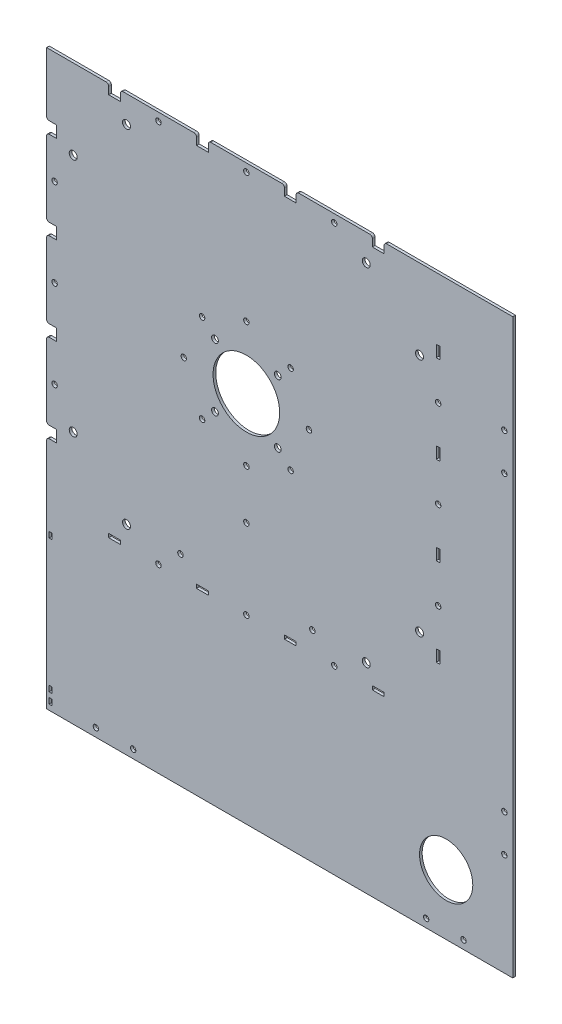
SolidWorks part; units mm, degrees
ref_plane "前视基准面" through (0, 0, 0) normal (0, 0, 1) x (1, 0, 0)
ref_plane "上视基准面" through (0, 0, 0) normal (0, 1, 0) x (1, 0, 0)
ref_plane "右视基准面" through (0, 0, 0) normal (1, 0, 0) x (0, 0, -1)
sketch "草图1" plane through (0, 0, 0) normal (0, 0, 1) x (1, 0, 0)
  line L0 (1.4571, -21.1871) -> (1.4571, -41.1871) construction
  line L2 (1.4571, -21.1871) -> (1.4571, 44.8129) construction
  line L4 (151.4571, -41.1871) -> (151.4571, 108.8129)
  line L5 (151.4571, 108.8129) -> (-148.5429, 108.8129)
  line L6 (-148.5429, 108.8129) -> (-148.5429, -191.1871)
  line L7 (-148.5429, -191.1871) -> (151.4571, -191.1871)
  line L8 (151.4571, -191.1871) -> (151.4571, -41.1871)
  line L9 (-148.5429, -41.1871) -> (-161.9412, -41.1871) construction
  line L10 (1.4571, -191.1871) -> (1.4571, -181.0361) construction
  circle A6 centre (1.4571, -21.1871) radius 241.4173 construction
  circle A9 centre (1.4571, -41.1871) radius 25
  circle A10 centre (25.0271, -17.6171) radius 2.55
  circle A11 centre (25.0271, -64.7571) radius 2.55
  circle A12 centre (-22.1129, -64.7571) radius 2.55
  circle A13 centre (-22.1129, -17.6171) radius 2.55
  circle A14 centre (115.1844, -53.0393) radius 12.2821 construction
  dimension "D1" = 50
  dimension "D4" = 5.1
  dimension "D2" = 300
  dimension "D3" = 300
  dimension "D5" = 23.57
  dimension "D6" = 23.57
  dimension "D7" = 4
extrude "凸台-拉伸1" add sketch "草图1" along normal blind 2
sketch "草图3" plane through (0, 0, 2) normal (0, 0, 1) x (1, 0, 0)
  line L1 (96.0571, -183.7871) -> (104.8571, -183.7871)
  line L13 (1.4571, -191.1871) -> (1.4571, -185.1871) construction
  line L14 (-148.5429, -191.1871) -> (151.4571, -191.1871) construction
  line L15 (1.4571, -185.1871) -> (34.4571, -185.1871) construction
  line L16 (34.4571, -185.1871) -> (67.4571, -185.1871) construction
  line L17 (30.0571, -183.7871) -> (38.8571, -183.7871)
  line L18 (30.0571, -183.7871) -> (30.0571, -186.5871)
  line L19 (30.0571, -186.5871) -> (38.8571, -186.5871)
  line L20 (38.8571, -183.7871) -> (38.8571, -186.5871)
  line L21 (30.0571, -183.7871) -> (38.8571, -186.5871) construction
  line L22 (30.0571, -186.5871) -> (38.8571, -183.7871) construction
  line L23 (67.4571, -185.1871) -> (100.4571, -185.1871) construction
  line L24 (96.0571, -183.7871) -> (96.0571, -186.5871)
  line L25 (96.0571, -186.5871) -> (104.8571, -186.5871)
  line L26 (96.0571, -186.5871) -> (104.8571, -183.7871) construction
  line L27 (104.8571, -186.5871) -> (104.8571, -183.7871)
  line L28 (-35.9429, -183.7871) -> (-35.9429, -186.5871)
  line L29 (-27.1429, -183.7871) -> (-35.9429, -183.7871)
  line L30 (-27.1429, -183.7871) -> (-27.1429, -186.5871)
  line L31 (-27.1429, -186.5871) -> (-35.9429, -186.5871)
  line L32 (-93.1429, -183.7871) -> (-93.1429, -186.5871)
  line L33 (-101.9429, -186.5871) -> (-101.9429, -183.7871)
  line L34 (-93.1429, -183.7871) -> (-101.9429, -183.7871)
  line L35 (-93.1429, -186.5871) -> (-101.9429, -186.5871)
  line L36 (-141.1429, 53.4129) -> (-141.1429, 62.2129)
  line L37 (-143.9429, 53.4129) -> (-143.9429, 62.2129)
  line L38 (-143.9429, 62.2129) -> (-141.1429, 62.2129)
  line L39 (-141.1429, 53.4129) -> (-143.9429, 53.4129)
  line L40 (-141.1429, -12.5871) -> (-141.1429, -3.7871)
  line L41 (-141.1429, -3.7871) -> (-143.9429, -3.7871)
  line L42 (-143.9429, -12.5871) -> (-143.9429, -3.7871)
  line L43 (-141.1429, -12.5871) -> (-143.9429, -12.5871)
  line L44 (-141.1429, -69.7871) -> (-143.9429, -69.7871)
  line L45 (-141.1429, -69.7871) -> (-141.1429, -78.5871)
  line L46 (-143.9429, -69.7871) -> (-143.9429, -78.5871)
  line L47 (-141.1429, -78.5871) -> (-143.9429, -78.5871)
  line L48 (-141.1429, -135.7871) -> (-141.1429, -144.5871)
  line L49 (-143.9429, -135.7871) -> (-143.9429, -144.5871)
  line L50 (-141.1429, -135.7871) -> (-143.9429, -135.7871)
  line L51 (-143.9429, -144.5871) -> (-141.1429, -144.5871)
  line L52 (96.0571, 101.4129) -> (104.8571, 101.4129)
  line L53 (96.0571, 104.2129) -> (104.8571, 104.2129)
  line L54 (104.8571, 104.2129) -> (104.8571, 101.4129)
  line L55 (96.0571, 101.4129) -> (96.0571, 104.2129)
  line L56 (30.0571, 101.4129) -> (38.8571, 101.4129)
  line L57 (38.8571, 101.4129) -> (38.8571, 104.2129)
  line L58 (30.0571, 104.2129) -> (38.8571, 104.2129)
  line L59 (30.0571, 101.4129) -> (30.0571, 104.2129)
  line L60 (-27.1429, 101.4129) -> (-27.1429, 104.2129)
  line L61 (-27.1429, 101.4129) -> (-35.9429, 101.4129)
  line L62 (-27.1429, 104.2129) -> (-35.9429, 104.2129)
  line L63 (-35.9429, 101.4129) -> (-35.9429, 104.2129)
  line L64 (-93.1429, 101.4129) -> (-101.9429, 101.4129)
  line L65 (-93.1429, 104.2129) -> (-101.9429, 104.2129)
  line L66 (-93.1429, 101.4129) -> (-93.1429, 104.2129)
  line L67 (-101.9429, 104.2129) -> (-101.9429, 101.4129)
  line L68 (144.0571, -135.7871) -> (144.0571, -144.5871)
  line L69 (146.8571, -135.7871) -> (146.8571, -144.5871)
  line L70 (146.8571, -144.5871) -> (144.0571, -144.5871)
  line L71 (144.0571, -135.7871) -> (146.8571, -135.7871)
  line L72 (144.0571, -69.7871) -> (144.0571, -78.5871)
  line L73 (144.0571, -78.5871) -> (146.8571, -78.5871)
  line L74 (146.8571, -69.7871) -> (146.8571, -78.5871)
  line L75 (144.0571, -69.7871) -> (146.8571, -69.7871)
  line L76 (144.0571, -12.5871) -> (146.8571, -12.5871)
  line L77 (144.0571, -12.5871) -> (144.0571, -3.7871)
  line L78 (146.8571, -12.5871) -> (146.8571, -3.7871)
  line L79 (144.0571, -3.7871) -> (146.8571, -3.7871)
  line L80 (144.0571, 53.4129) -> (144.0571, 62.2129)
  line L81 (146.8571, 53.4129) -> (146.8571, 62.2129)
  line L82 (144.0571, 53.4129) -> (146.8571, 53.4129)
  line L83 (146.8571, 62.2129) -> (144.0571, 62.2129)
  line L84 (50.9571, -185.1871) -> (50.9571, -170.1871) construction
  line L85 (17.9571, -185.1871) -> (17.9571, -170.1871) construction
  line L86 (-48.0429, -170.1871) -> (-15.0429, -170.1871) construction
  line L91 (-31.5429, -170.1871) -> (-31.5429, -155.1871) construction
  line L92 (100.4571, -185.1871) -> (104.8571, -186.5871) construction
  line L93 (-31.5429, -155.1871) -> (1.4571, -155.1871) construction
  line L95 (1.4571, -155.1871) -> (34.4571, -155.1871) construction
  circle A0 centre (1.4571, -185.1871) radius 2.05
  circle A1 centre (67.4571, -185.1871) radius 2.05
  circle A2 centre (-64.5429, -185.1871) radius 2.05
  circle A3 centre (-142.5429, 24.8129) radius 2.05
  circle A4 centre (-142.5429, -41.1871) radius 2.05
  circle A5 centre (-142.5429, -107.1871) radius 2.05
  circle A6 centre (67.4571, 102.8129) radius 2.05
  circle A7 centre (1.4571, 102.8129) radius 2.05
  circle A8 centre (-64.5429, 102.8129) radius 2.05
  circle A9 centre (145.4571, -107.1871) radius 2.05
  circle A10 centre (145.4571, -41.1871) radius 2.05
  circle A11 centre (145.4571, 24.8129) radius 2.05
  circle A15 centre (17.9571, -170.1871) radius 2 construction
  circle A16 centre (-15.0429, -170.1871) radius 2 construction
  circle A17 centre (50.9571, -170.1871) radius 2.05
  circle A18 centre (-48.0429, -170.1871) radius 2.05
  circle A19 centre (-31.5429, -155.1871) radius 2.05 construction
  circle A20 centre (34.4571, -155.1871) radius 2.05 construction
  circle A22 centre (1.4571, -155.1871) radius 2 construction
  circle A23 centre (1.4571, -41.1871) radius 47 construction
  circle A24 centre (1.4571, -88.1871) radius 2.05
  circle A25 centre (-31.7769, -74.4212) radius 2.05
  circle A26 centre (-45.5429, -41.1871) radius 2.05
  circle A27 centre (-31.7769, -7.9531) radius 2.05
  circle A28 centre (1.4571, 5.8129) radius 2.05
  circle A29 centre (34.6912, -7.9531) radius 2.05
  circle A30 centre (48.4571, -41.1871) radius 2.05
  circle A31 centre (34.6912, -74.4212) radius 2.05
  circle A32 centre (1.4571, -125.1871) radius 2.05
  dimension "D1" = 8.8
  dimension "D3" = 4
  dimension "D4" = 8
  dimension "D5" = 30
  dimension "D6" = 4.1
  dimension "D7" = 94
  dimension "D8" = 4.1
  dimension "D9" = 8.8
  dimension "D2" = 2.8
  dimension "D10" = 2.8
extrude "切除-拉伸2" cut sketch "草图3" against normal blind 4
sketch "草图6" plane through (0, 0, 2) normal (0, 0, 1) x (1, 0, 0)
sketch "草图7" plane through (0, 0, 2) normal (0, 0, 1) x (1, 0, 0)
  line L5 (-148.5429, -171.1871) -> (151.4571, -171.1871) construction
  line L6 (-148.5429, 108.8129) -> (-148.5429, -191.1871) construction
  line L7 (151.4571, -191.1871) -> (151.4571, 108.8129) construction
  line L8 (-148.5429, -191.1871) -> (151.4571, -191.1871) construction
  circle A0 centre (-88.5429, -171.1871) radius 3
  circle A1 centre (91.4571, -171.1871) radius 3
  circle A2 centre (-128.5429, 48.8129) radius 3
  circle A3 centre (-128.5429, -131.1871) radius 3
  circle A4 centre (91.4571, 88.8129) radius 3
  circle A5 centre (-88.5429, 88.8129) radius 3
  circle A6 centre (131.4571, -131.1871) radius 3
  circle A7 centre (131.4571, 48.8129) radius 3
  dimension "D2" = 6
  dimension "D4" = 60
  dimension "D1" = 20
  dimension "D3" = 60
  dimension "D5" = 4
extrude "切除-拉伸3" cut sketch "草图7" against normal blind 10
sketch "草图9" plane through (0, 0, 2) normal (0, 0, 1) x (1, 0, 0)
  line L0 (151.4571, 108.8129) -> (201.4571, 108.8129)
  line L1 (151.4571, -191.1871) -> (201.4571, -191.1871) construction
  line L2 (201.4571, -191.1871) -> (201.4571, 108.8129)
  line L3 (151.4571, 108.8129) -> (151.4571, -191.1871)
  line L6 (201.4571, -321.1871) -> (201.4571, -191.1871)
  line L7 (-148.5429, -191.1871) -> (151.4571, -191.1871)
  line L11 (201.4571, -323.3871) -> (203.6571, -321.1871) construction
  line L12 (201.4571, -321.1871) -> (203.6571, -321.1871) construction
  line L13 (201.4571, -321.1871) -> (201.4571, -323.3871) construction
  line L14 (201.4571, -323.3871) -> (203.6571, -323.3871) construction
  line L15 (203.6571, -321.1871) -> (203.6571, -323.3871) construction
  line L16 (-150.7429, -323.3871) -> (-148.5429, -321.1871) construction
  line L17 (-148.5429, -321.1871) -> (-150.7429, -321.1871) construction
  line L18 (-148.5429, -321.1871) -> (-148.5429, -323.3871) construction
  line L19 (-148.5429, -323.3871) -> (-150.7429, -323.3871) construction
  line L20 (-150.7429, -321.1871) -> (-150.7429, -323.3871) construction
  line L21 (-146.7429, -315.0371) -> (-144.4429, -315.0371) construction
  line L22 (-144.4429, -317.1871) -> (-146.7429, -317.1871)
  line L23 (-144.4429, -317.1871) -> (-144.4429, -312.8871)
  line L24 (-144.4429, -312.8871) -> (-146.7429, -312.8871)
  line L25 (-146.7429, -317.1871) -> (-146.7429, -312.8871)
  line L26 (-144.4429, -309.1871) -> (-146.7429, -309.1871)
  line L27 (-144.4429, -309.1871) -> (-144.4429, -304.8871)
  line L28 (-144.4429, -304.8871) -> (-146.7429, -304.8871)
  line L29 (-146.7429, -309.1871) -> (-146.7429, -304.8871)
  line L30 (-146.7429, -307.0371) -> (-144.4429, -307.0371) construction
  line L31 (-148.5429, -321.1871) -> (201.4571, -321.1871)
  line L32 (-148.5429, -321.1871) -> (-148.5429, -191.1871)
  line L33 (-111.5429, -314.8871) -> (-83.5429, -314.8871) construction
  line L34 (-144.4429, -204.8871) -> (-146.7429, -204.8871)
  line L35 (-144.4429, -204.8871) -> (-144.4429, -209.1871)
  line L36 (-144.4429, -209.1871) -> (-146.7429, -209.1871)
  line L37 (-146.7429, -204.8871) -> (-146.7429, -209.1871)
  line L38 (26.4571, -321.1871) -> (26.4571, -291.6065) construction
  line L39 (182.6983, -321.1871) -> (182.6983, 108.8129) construction
  line L40 (182.6983, -106.1871) -> (169.8123, -106.1871) construction
  line L41 (195.1571, -244.1871) -> (195.1571, -216.1871) construction
  line L42 (-146.7429, -207.0371) -> (-144.4429, -207.0371) construction
  arc A1 (-148.5429, -303.223) -> (-130.5787, -321.1871) centre (-148.5429, -321.1871) ccw construction
  circle A2 centre (202.5571, -322.2871) radius 1.5556 construction
  circle A3 centre (-149.6429, -322.2871) radius 1.5556 construction
  circle A4 centre (151.4571, -275.7999) radius 20
  circle A5 centre (-111.5429, -314.8871) radius 2
  circle A6 centre (-83.5429, -314.8871) radius 2
  circle A7 centre (136.4571, -314.8871) radius 2
  circle A8 centre (164.4571, -314.8871) radius 2
  circle A9 centre (195.1571, -244.1871) radius 2
  circle A10 centre (195.1571, -216.1871) radius 2
  circle A11 centre (195.1571, 3.8129) radius 2
  circle A12 centre (195.1571, 31.8129) radius 2
  point P32 (-149.6429, -321.1871)
  point P65 (-145.5929, -207.0371)
  dimension "D12" = 4.3
  dimension "D13" = 28
  dimension "D14" = 4
  dimension "D15" = 4
  dimension "D18" = 4
  dimension "D20" = 4
  dimension "D1" = 50
  dimension "D2" = 130
  dimension "D3" = 2.2
  dimension "D4" = 2.2
  dimension "D5" = 2.2
  dimension "D6" = 4.3
  dimension "D7" = 4.3
  dimension "D8" = 4
  dimension "D9" = 8
  dimension "D10" = 2.3
  dimension "D11" = 2.3
  dimension "D16" = 6.3
  dimension "D17" = 220
  dimension "D19" = 28
  dimension "D21" = 6.3
  dimension "D22" = 220
  dimension "D23" = 100
  dimension "D24" = 2.3
extrude "凸台-拉伸3" add sketch "草图9" against normal blind 2
sketch "草图10" plane through (0, 0, 2) normal (0, 0, 1) x (1, 0, 0)
  line L1 (-143.9429, 62.2129) -> (-151.3588, 62.2129)
  line L2 (-143.9429, 62.2129) -> (-143.9429, 53.4129)
  line L3 (-143.9429, 53.4129) -> (-151.3588, 53.4129)
  line L4 (-151.3588, 62.2129) -> (-151.3588, 53.4129)
  line L5 (-143.9429, -3.7871) -> (-155.5855, -3.7871)
  line L6 (-143.9429, -3.7871) -> (-143.9429, -12.5871)
  line L7 (-143.9429, -12.5871) -> (-155.5855, -12.5871)
  line L8 (-155.5855, -3.7871) -> (-155.5855, -12.5871)
  line L9 (-143.9429, -69.7871) -> (-153.446, -69.7871)
  line L10 (-143.9429, -69.7871) -> (-143.9429, -78.5871)
  line L11 (-143.9429, -78.5871) -> (-153.446, -78.5871)
  line L12 (-153.446, -69.7871) -> (-153.446, -78.5871)
  line L13 (-143.9429, -135.7871) -> (-155.5855, -135.7871)
  line L14 (-143.9429, -135.7871) -> (-143.9429, -144.5871)
  line L15 (-143.9429, -144.5871) -> (-155.5855, -144.5871)
  line L16 (-155.5855, -135.7871) -> (-155.5855, -144.5871)
  line L17 (-101.9429, 104.2129) -> (-93.1429, 104.2129)
  line L18 (-101.9429, 104.2129) -> (-101.9429, 114.1666)
  line L19 (-101.9429, 114.1666) -> (-93.1429, 114.1666)
  line L20 (-93.1429, 104.2129) -> (-93.1429, 114.1666)
  line L21 (-35.9429, 104.2129) -> (-27.1429, 104.2129)
  line L22 (-35.9429, 104.2129) -> (-35.9429, 110.4494)
  line L23 (-35.9429, 110.4494) -> (-27.1429, 110.4494)
  line L24 (-27.1429, 104.2129) -> (-27.1429, 110.4494)
  line L25 (30.0571, 104.2129) -> (38.8571, 104.2129)
  line L26 (30.0571, 104.2129) -> (30.0571, 115.999)
  line L27 (30.0571, 115.999) -> (38.8571, 115.999)
  line L28 (38.8571, 104.2129) -> (38.8571, 115.999)
  line L29 (96.0571, 104.2129) -> (104.8571, 104.2129)
  line L30 (96.0571, 104.2129) -> (96.0571, 117.0027)
  line L31 (96.0571, 117.0027) -> (104.8571, 117.0027)
  line L32 (104.8571, 104.2129) -> (104.8571, 117.0027)
extrude "切除-拉伸4" cut sketch "草图10" against normal blind 2
fillet "圆角1" radius 2 16 edges at (96.0571, 108.8129, 1) (104.8571, 108.8129, 1) (30.0571, 108.8129, 1) (38.8571, 108.8129, 1) (-35.9429, 108.8129, 1) (-27.1429, 108.8129, 1) (-148.5429, -12.5871, 1) (-148.5429, -3.7871, 1) (-148.5429, -78.5871, 1) (-148.5429, -69.7871, 1) (-148.5429, -144.5871, 1) (-148.5429, -135.7871, 1) (-101.9429, 108.8129, 1) (-93.1429, 108.8129, 1) (-148.5429, 53.4129, 1) (-148.5429, 62.2129, 1)
